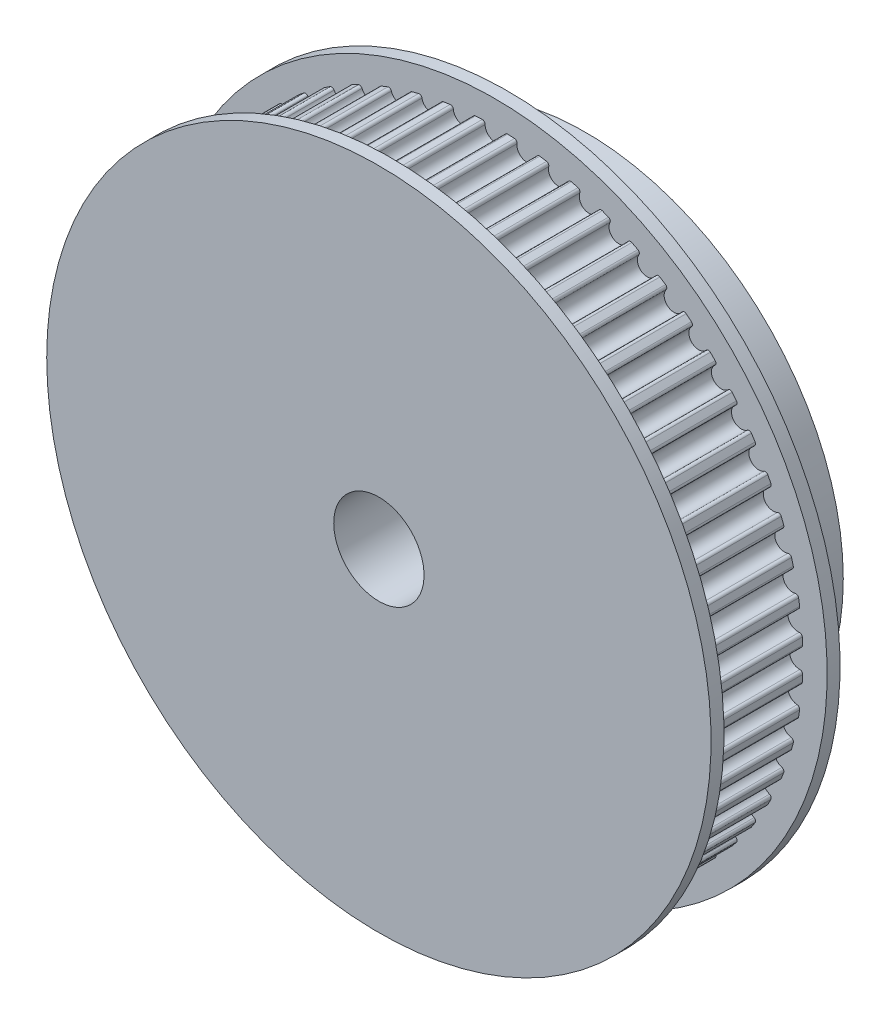
SolidWorks part; units mm, degrees
ref_plane "Front Plane" through (0, 0, 0) normal (0, 0, 1) x (1, 0, 0)
ref_plane "Top Plane" through (0, 0, 0) normal (0, 1, 0) x (1, 0, 0)
ref_plane "Right Plane" through (0, 0, 0) normal (1, 0, 0) x (0, 0, -1)
sketch "Sketch1" plane through (0, 0, 0) normal (0, 0, 1) x (1, 0, 0)
  arc A2 (3.0256, 47.649) -> (1.9717, 47.7043) centre (0, 0) ccw
  arc A3 (0, 45.685) -> (1.5242, 47.2604) centre (0, 47.21) ccw
  arc A4 (1.9717, 47.7043) -> (1.5242, 47.2604) centre (1.9539, 47.2746) ccw
  arc A5 (3.4242, 47.1608) -> (4.7754, 45.4347) centre (4.9348, 46.9514) ccw
  arc A6 (3.4242, 47.1608) -> (3.0256, 47.649) centre (2.9983, 47.2199) ccw
  arc A7 (4.7754, 45.4347) -> (6.4559, 46.8422) centre (4.9348, 46.9514) ccw
  arc A8 (6.9473, 47.2368) -> (6.4559, 46.8422) centre (6.8848, 46.8114) ccw
  arc A9 (7.9897, 47.0718) -> (6.9473, 47.2368) centre (0, 0) ccw
  arc A10 (8.3351, 46.5446) -> (7.9897, 47.0718) centre (7.9177, 46.6478) ccw
  arc A11 (8.3351, 46.5446) -> (9.4984, 44.6867) centre (9.8155, 46.1783) ccw
  arc A12 (9.4984, 44.6867) -> (11.3169, 45.9108) centre (9.8155, 46.1783) ccw
  arc A13 (11.8469, 46.2519) -> (11.3169, 45.9108) centre (11.7402, 45.8353) ccw
  arc A14 (12.8662, 45.9787) -> (11.8469, 46.2519) centre (0, 0) ccw
  arc A15 (13.1547, 45.4183) -> (12.8662, 45.9787) centre (12.7504, 45.5647) ccw
  arc A16 (13.1547, 45.4183) -> (14.1174, 43.449) centre (14.5887, 44.8994) ccw
  arc A17 (14.1174, 43.449) -> (16.0538, 44.4763) centre (14.5887, 44.8994) ccw
  arc A18 (16.6166, 44.7602) -> (16.0538, 44.4763) centre (16.467, 44.3571) ccw
  arc A19 (17.6018, 44.382) -> (16.6166, 44.7602) centre (0, 0) ccw
  arc A20 (17.8301, 43.7945) -> (17.6018, 44.382) centre (17.4433, 43.9823) ccw
  arc A21 (17.8301, 43.7945) -> (18.5818, 41.7353) centre (19.202, 43.1285) ccw
  arc A22 (18.5818, 41.7353) -> (20.6149, 42.5546) centre (19.202, 43.1285) ccw
  arc A23 (21.2043, 42.7781) -> (20.6149, 42.5546) centre (21.0133, 42.3928) ccw
  arc A24 (22.1446, 42.299) -> (21.2043, 42.7781) centre (0, 0) ccw
  arc A25 (22.3102, 41.6908) -> (22.1446, 42.299) centre (21.9452, 41.918) ccw
  arc A26 (22.3102, 41.6908) -> (22.8425, 39.5644) centre (23.605, 40.8851) ccw
  arc A27 (22.8425, 39.5644) -> (24.9502, 40.1666) centre (23.605, 40.8851) ccw
  arc A28 (25.5597, 40.3273) -> (24.9502, 40.1666) centre (25.3295, 39.9641) ccw
  arc A29 (26.4447, 39.7525) -> (25.5597, 40.3273) centre (0, 0) ccw
  arc A30 (26.5459, 39.1304) -> (26.4447, 39.7525) centre (26.2066, 39.3945) ccw
  arc A31 (26.5459, 39.1304) -> (26.853, 36.9599) centre (27.7493, 38.1937) ccw
  arc A32 (26.853, 36.9599) -> (29.0121, 37.3386) centre (27.7493, 38.1937) ccw
  arc A33 (29.635, 37.4346) -> (29.0121, 37.3386) centre (29.3681, 37.0975) ccw
  arc A34 (30.4551, 36.7705) -> (29.635, 37.4346) centre (0, 0) ccw
  arc A35 (30.4907, 36.1412) -> (30.4551, 36.7705) centre (30.1809, 36.4393) ccw
  arc A36 (30.4907, 36.1412) -> (30.5692, 33.9506) centre (31.5897, 35.0839) ccw
  arc A37 (30.5692, 33.9506) -> (32.7561, 34.1015) centre (31.5897, 35.0839) ccw
  arc A38 (33.3856, 34.1319) -> (32.7561, 34.1015) centre (33.085, 33.8245) ccw
  arc A39 (34.1319, 33.3856) -> (33.3856, 34.1319) centre (0, 0) ccw
  arc A40 (34.1015, 32.7561) -> (34.1319, 33.3856) centre (33.8245, 33.085) ccw
  arc A41 (34.1015, 32.7561) -> (33.9506, 30.5692) centre (35.0839, 31.5897) ccw
  arc A42 (33.9506, 30.5692) -> (36.1412, 30.4907) centre (35.0839, 31.5897) ccw
  arc A43 (36.7705, 30.4551) -> (36.1412, 30.4907) centre (36.4393, 30.1809) ccw
  arc A44 (37.4346, 29.635) -> (36.7705, 30.4551) centre (0, 0) ccw
  arc A45 (37.3386, 29.0121) -> (37.4346, 29.635) centre (37.0975, 29.3681) ccw
  arc A46 (37.3386, 29.0121) -> (36.9599, 26.853) centre (38.1937, 27.7493) ccw
  arc A47 (36.9599, 26.853) -> (39.1304, 26.5459) centre (38.1937, 27.7493) ccw
  arc A48 (39.7525, 26.4447) -> (39.1304, 26.5459) centre (39.3945, 26.2066) ccw
  arc A49 (40.3273, 25.5597) -> (39.7525, 26.4447) centre (0, 0) ccw
  arc A50 (40.1666, 24.9502) -> (40.3273, 25.5597) centre (39.9641, 25.3295) ccw
  arc A51 (40.1666, 24.9502) -> (39.5644, 22.8425) centre (40.8851, 23.605) ccw
  arc A52 (39.5644, 22.8425) -> (41.6908, 22.3102) centre (40.8851, 23.605) ccw
  arc A53 (42.299, 22.1446) -> (41.6908, 22.3102) centre (41.918, 21.9452) ccw
  arc A54 (42.7781, 21.2043) -> (42.299, 22.1446) centre (0, 0) ccw
  arc A55 (42.5546, 20.6149) -> (42.7781, 21.2043) centre (42.3928, 21.0133) ccw
  arc A56 (42.5546, 20.6149) -> (41.7353, 18.5818) centre (43.1285, 19.202) ccw
  arc A57 (41.7353, 18.5818) -> (43.7945, 17.8301) centre (43.1285, 19.202) ccw
  arc A58 (44.382, 17.6018) -> (43.7945, 17.8301) centre (43.9823, 17.4433) ccw
  arc A59 (44.7602, 16.6166) -> (44.382, 17.6018) centre (0, 0) ccw
  arc A60 (44.4763, 16.0538) -> (44.7602, 16.6166) centre (44.3571, 16.467) ccw
  arc A61 (44.4763, 16.0538) -> (43.449, 14.1174) centre (44.8994, 14.5887) ccw
  arc A62 (43.449, 14.1174) -> (45.4183, 13.1547) centre (44.8994, 14.5887) ccw
  arc A63 (45.9787, 12.8662) -> (45.4183, 13.1547) centre (45.5647, 12.7504) ccw
  arc A64 (46.2519, 11.8469) -> (45.9787, 12.8662) centre (0, 0) ccw
  arc A65 (45.9108, 11.3169) -> (46.2519, 11.8469) centre (45.8353, 11.7402) ccw
  arc A66 (45.9108, 11.3169) -> (44.6867, 9.4984) centre (46.1783, 9.8155) ccw
  arc A67 (44.6867, 9.4984) -> (46.5446, 8.3351) centre (46.1783, 9.8155) ccw
  arc A68 (47.0718, 7.9897) -> (46.5446, 8.3351) centre (46.6478, 7.9177) ccw
  arc A69 (47.2368, 6.9473) -> (47.0718, 7.9897) centre (0, 0) ccw
  arc A70 (46.8422, 6.4559) -> (47.2368, 6.9473) centre (46.8114, 6.8848) ccw
  arc A71 (46.8422, 6.4559) -> (45.4347, 4.7754) centre (46.9514, 4.9348) ccw
  arc A72 (45.4347, 4.7754) -> (47.1608, 3.4242) centre (46.9514, 4.9348) ccw
  arc A73 (47.649, 3.0256) -> (47.1608, 3.4242) centre (47.2199, 2.9983) ccw
  arc A74 (47.7043, 1.9717) -> (47.649, 3.0256) centre (0, 0) ccw
  arc A75 (47.2604, 1.5242) -> (47.7043, 1.9717) centre (47.2746, 1.9539) ccw
  arc A76 (47.2604, 1.5242) -> (45.685, 0) centre (47.21, 0) ccw
  arc A77 (45.685, 0) -> (47.2604, -1.5242) centre (47.21, 0) ccw
  arc A78 (47.7043, -1.9717) -> (47.2604, -1.5242) centre (47.2746, -1.9539) ccw
  arc A79 (47.649, -3.0256) -> (47.7043, -1.9717) centre (0, 0) ccw
  arc A80 (47.1608, -3.4242) -> (47.649, -3.0256) centre (47.2199, -2.9983) ccw
  arc A81 (47.1608, -3.4242) -> (45.4347, -4.7754) centre (46.9514, -4.9348) ccw
  arc A82 (45.4347, -4.7754) -> (46.8422, -6.4559) centre (46.9514, -4.9348) ccw
  arc A83 (47.2368, -6.9473) -> (46.8422, -6.4559) centre (46.8114, -6.8848) ccw
  arc A84 (47.0718, -7.9897) -> (47.2368, -6.9473) centre (0, 0) ccw
  arc A85 (46.5446, -8.3351) -> (47.0718, -7.9897) centre (46.6478, -7.9177) ccw
  arc A86 (46.5446, -8.3351) -> (44.6867, -9.4984) centre (46.1783, -9.8155) ccw
  arc A87 (44.6867, -9.4984) -> (45.9108, -11.3169) centre (46.1783, -9.8155) ccw
  arc A88 (46.2519, -11.8469) -> (45.9108, -11.3169) centre (45.8353, -11.7402) ccw
  arc A89 (45.9787, -12.8662) -> (46.2519, -11.8469) centre (0, 0) ccw
  arc A90 (45.4183, -13.1547) -> (45.9787, -12.8662) centre (45.5647, -12.7504) ccw
  arc A91 (45.4183, -13.1547) -> (43.449, -14.1174) centre (44.8994, -14.5887) ccw
  arc A92 (43.449, -14.1174) -> (44.4763, -16.0538) centre (44.8994, -14.5887) ccw
  arc A93 (44.7602, -16.6166) -> (44.4763, -16.0538) centre (44.3571, -16.467) ccw
  arc A94 (44.382, -17.6018) -> (44.7602, -16.6166) centre (0, 0) ccw
  arc A95 (43.7945, -17.8301) -> (44.382, -17.6018) centre (43.9823, -17.4433) ccw
  arc A96 (43.7945, -17.8301) -> (41.7353, -18.5818) centre (43.1285, -19.202) ccw
  arc A97 (41.7353, -18.5818) -> (42.5546, -20.6149) centre (43.1285, -19.202) ccw
  arc A98 (42.7781, -21.2043) -> (42.5546, -20.6149) centre (42.3928, -21.0133) ccw
  arc A99 (42.299, -22.1446) -> (42.7781, -21.2043) centre (0, 0) ccw
  arc A100 (41.6908, -22.3102) -> (42.299, -22.1446) centre (41.918, -21.9452) ccw
  arc A101 (41.6908, -22.3102) -> (39.5644, -22.8425) centre (40.8851, -23.605) ccw
  arc A102 (39.5644, -22.8425) -> (40.1666, -24.9502) centre (40.8851, -23.605) ccw
  arc A103 (40.3273, -25.5597) -> (40.1666, -24.9502) centre (39.9641, -25.3295) ccw
  arc A104 (39.7525, -26.4447) -> (40.3273, -25.5597) centre (0, 0) ccw
  arc A105 (39.1304, -26.5459) -> (39.7525, -26.4447) centre (39.3945, -26.2066) ccw
  arc A106 (39.1304, -26.5459) -> (36.9599, -26.853) centre (38.1937, -27.7493) ccw
  arc A107 (36.9599, -26.853) -> (37.3386, -29.0121) centre (38.1937, -27.7493) ccw
  arc A108 (37.4346, -29.635) -> (37.3386, -29.0121) centre (37.0975, -29.3681) ccw
  arc A109 (36.7705, -30.4551) -> (37.4346, -29.635) centre (0, 0) ccw
  arc A110 (36.1412, -30.4907) -> (36.7705, -30.4551) centre (36.4393, -30.1809) ccw
  arc A111 (36.1412, -30.4907) -> (33.9506, -30.5692) centre (35.0839, -31.5897) ccw
  arc A112 (33.9506, -30.5692) -> (34.1015, -32.7561) centre (35.0839, -31.5897) ccw
  arc A113 (34.1319, -33.3856) -> (34.1015, -32.7561) centre (33.8245, -33.085) ccw
  arc A114 (33.3856, -34.1319) -> (34.1319, -33.3856) centre (0, 0) ccw
  arc A115 (32.7561, -34.1015) -> (33.3856, -34.1319) centre (33.085, -33.8245) ccw
  arc A116 (32.7561, -34.1015) -> (30.5692, -33.9506) centre (31.5897, -35.0839) ccw
  arc A117 (30.5692, -33.9506) -> (30.4907, -36.1412) centre (31.5897, -35.0839) ccw
  arc A118 (30.4551, -36.7705) -> (30.4907, -36.1412) centre (30.1809, -36.4393) ccw
  arc A119 (29.635, -37.4346) -> (30.4551, -36.7705) centre (0, 0) ccw
  arc A120 (29.0121, -37.3386) -> (29.635, -37.4346) centre (29.3681, -37.0975) ccw
  arc A121 (29.0121, -37.3386) -> (26.853, -36.9599) centre (27.7493, -38.1937) ccw
  arc A122 (26.853, -36.9599) -> (26.5459, -39.1304) centre (27.7493, -38.1937) ccw
  arc A123 (26.4447, -39.7525) -> (26.5459, -39.1304) centre (26.2066, -39.3945) ccw
  arc A124 (25.5597, -40.3273) -> (26.4447, -39.7525) centre (0, 0) ccw
  arc A125 (24.9502, -40.1666) -> (25.5597, -40.3273) centre (25.3295, -39.9641) ccw
  arc A126 (24.9502, -40.1666) -> (22.8425, -39.5644) centre (23.605, -40.8851) ccw
  arc A127 (22.8425, -39.5644) -> (22.3102, -41.6908) centre (23.605, -40.8851) ccw
  arc A128 (22.1446, -42.299) -> (22.3102, -41.6908) centre (21.9452, -41.918) ccw
  arc A129 (21.2043, -42.7781) -> (22.1446, -42.299) centre (0, 0) ccw
  arc A130 (20.6149, -42.5546) -> (21.2043, -42.7781) centre (21.0133, -42.3928) ccw
  arc A131 (20.6149, -42.5546) -> (18.5818, -41.7353) centre (19.202, -43.1285) ccw
  arc A132 (18.5818, -41.7353) -> (17.8301, -43.7945) centre (19.202, -43.1285) ccw
  arc A133 (17.6018, -44.382) -> (17.8301, -43.7945) centre (17.4433, -43.9823) ccw
  arc A134 (16.6166, -44.7602) -> (17.6018, -44.382) centre (0, 0) ccw
  arc A135 (16.0538, -44.4763) -> (16.6166, -44.7602) centre (16.467, -44.3571) ccw
  arc A136 (16.0538, -44.4763) -> (14.1174, -43.449) centre (14.5887, -44.8994) ccw
  arc A137 (14.1174, -43.449) -> (13.1547, -45.4183) centre (14.5887, -44.8994) ccw
  arc A138 (12.8662, -45.9787) -> (13.1547, -45.4183) centre (12.7504, -45.5647) ccw
  arc A139 (11.8469, -46.2519) -> (12.8662, -45.9787) centre (0, 0) ccw
  arc A140 (11.3169, -45.9108) -> (11.8469, -46.2519) centre (11.7402, -45.8353) ccw
  arc A141 (11.3169, -45.9108) -> (9.4984, -44.6867) centre (9.8155, -46.1783) ccw
  arc A142 (9.4984, -44.6867) -> (8.3351, -46.5446) centre (9.8155, -46.1783) ccw
  arc A143 (7.9897, -47.0718) -> (8.3351, -46.5446) centre (7.9177, -46.6478) ccw
  arc A144 (6.9473, -47.2368) -> (7.9897, -47.0718) centre (0, 0) ccw
  arc A145 (6.4559, -46.8422) -> (6.9473, -47.2368) centre (6.8848, -46.8114) ccw
  arc A146 (6.4559, -46.8422) -> (4.7754, -45.4347) centre (4.9348, -46.9514) ccw
  arc A147 (4.7754, -45.4347) -> (3.4242, -47.1608) centre (4.9348, -46.9514) ccw
  arc A148 (3.0256, -47.649) -> (3.4242, -47.1608) centre (2.9983, -47.2199) ccw
  arc A149 (1.9717, -47.7043) -> (3.0256, -47.649) centre (0, 0) ccw
  arc A150 (1.5242, -47.2604) -> (1.9717, -47.7043) centre (1.9539, -47.2746) ccw
  arc A151 (1.5242, -47.2604) -> (0, -45.685) centre (0, -47.21) ccw
  arc A152 (0, -45.685) -> (-1.5242, -47.2604) centre (0, -47.21) ccw
  arc A153 (-1.9717, -47.7043) -> (-1.5242, -47.2604) centre (-1.9539, -47.2746) ccw
  arc A154 (-3.0256, -47.649) -> (-1.9717, -47.7043) centre (0, 0) ccw
  arc A155 (-3.4242, -47.1608) -> (-3.0256, -47.649) centre (-2.9983, -47.2199) ccw
  arc A156 (-3.4242, -47.1608) -> (-4.7754, -45.4347) centre (-4.9348, -46.9514) ccw
  arc A157 (-4.7754, -45.4347) -> (-6.4559, -46.8422) centre (-4.9348, -46.9514) ccw
  arc A158 (-6.9473, -47.2368) -> (-6.4559, -46.8422) centre (-6.8848, -46.8114) ccw
  arc A159 (-7.9897, -47.0718) -> (-6.9473, -47.2368) centre (0, 0) ccw
  arc A160 (-8.3351, -46.5446) -> (-7.9897, -47.0718) centre (-7.9177, -46.6478) ccw
  arc A161 (-8.3351, -46.5446) -> (-9.4984, -44.6867) centre (-9.8155, -46.1783) ccw
  arc A162 (-9.4984, -44.6867) -> (-11.3169, -45.9108) centre (-9.8155, -46.1783) ccw
  arc A163 (-11.8469, -46.2519) -> (-11.3169, -45.9108) centre (-11.7402, -45.8353) ccw
  arc A164 (-12.8662, -45.9787) -> (-11.8469, -46.2519) centre (0, 0) ccw
  arc A165 (-13.1547, -45.4183) -> (-12.8662, -45.9787) centre (-12.7504, -45.5647) ccw
  arc A166 (-13.1547, -45.4183) -> (-14.1174, -43.449) centre (-14.5887, -44.8994) ccw
  arc A167 (-14.1174, -43.449) -> (-16.0538, -44.4763) centre (-14.5887, -44.8994) ccw
  arc A168 (-16.6166, -44.7602) -> (-16.0538, -44.4763) centre (-16.467, -44.3571) ccw
  arc A169 (-17.6018, -44.382) -> (-16.6166, -44.7602) centre (0, 0) ccw
  arc A170 (-17.8301, -43.7945) -> (-17.6018, -44.382) centre (-17.4433, -43.9823) ccw
  arc A171 (-17.8301, -43.7945) -> (-18.5818, -41.7353) centre (-19.202, -43.1285) ccw
  arc A172 (-18.5818, -41.7353) -> (-20.6149, -42.5546) centre (-19.202, -43.1285) ccw
  arc A173 (-21.2043, -42.7781) -> (-20.6149, -42.5546) centre (-21.0133, -42.3928) ccw
  arc A174 (-22.1446, -42.299) -> (-21.2043, -42.7781) centre (0, 0) ccw
  arc A175 (-22.3102, -41.6908) -> (-22.1446, -42.299) centre (-21.9452, -41.918) ccw
  arc A176 (-22.3102, -41.6908) -> (-22.8425, -39.5644) centre (-23.605, -40.8851) ccw
  arc A177 (-22.8425, -39.5644) -> (-24.9502, -40.1666) centre (-23.605, -40.8851) ccw
  arc A178 (-25.5597, -40.3273) -> (-24.9502, -40.1666) centre (-25.3295, -39.9641) ccw
  arc A179 (-26.4447, -39.7525) -> (-25.5597, -40.3273) centre (0, 0) ccw
  arc A180 (-26.5459, -39.1304) -> (-26.4447, -39.7525) centre (-26.2066, -39.3945) ccw
  arc A181 (-26.5459, -39.1304) -> (-26.853, -36.9599) centre (-27.7493, -38.1937) ccw
  arc A182 (-26.853, -36.9599) -> (-29.0121, -37.3386) centre (-27.7493, -38.1937) ccw
  arc A183 (-29.635, -37.4346) -> (-29.0121, -37.3386) centre (-29.3681, -37.0975) ccw
  arc A184 (-30.4551, -36.7705) -> (-29.635, -37.4346) centre (0, 0) ccw
  arc A185 (-30.4907, -36.1412) -> (-30.4551, -36.7705) centre (-30.1809, -36.4393) ccw
  arc A186 (-30.4907, -36.1412) -> (-30.5692, -33.9506) centre (-31.5897, -35.0839) ccw
  arc A187 (-30.5692, -33.9506) -> (-32.7561, -34.1015) centre (-31.5897, -35.0839) ccw
  arc A188 (-33.3856, -34.1319) -> (-32.7561, -34.1015) centre (-33.085, -33.8245) ccw
  arc A189 (-34.1319, -33.3856) -> (-33.3856, -34.1319) centre (0, 0) ccw
  arc A190 (-34.1015, -32.7561) -> (-34.1319, -33.3856) centre (-33.8245, -33.085) ccw
  arc A191 (-34.1015, -32.7561) -> (-33.9506, -30.5692) centre (-35.0839, -31.5897) ccw
  arc A192 (-33.9506, -30.5692) -> (-36.1412, -30.4907) centre (-35.0839, -31.5897) ccw
  arc A193 (-36.7705, -30.4551) -> (-36.1412, -30.4907) centre (-36.4393, -30.1809) ccw
  arc A194 (-37.4346, -29.635) -> (-36.7705, -30.4551) centre (0, 0) ccw
  arc A195 (-37.3386, -29.0121) -> (-37.4346, -29.635) centre (-37.0975, -29.3681) ccw
  arc A196 (-37.3386, -29.0121) -> (-36.9599, -26.853) centre (-38.1937, -27.7493) ccw
  arc A197 (-36.9599, -26.853) -> (-39.1304, -26.5459) centre (-38.1937, -27.7493) ccw
  arc A198 (-39.7525, -26.4447) -> (-39.1304, -26.5459) centre (-39.3945, -26.2066) ccw
  arc A199 (-40.3273, -25.5597) -> (-39.7525, -26.4447) centre (0, 0) ccw
  arc A200 (-40.1666, -24.9502) -> (-40.3273, -25.5597) centre (-39.9641, -25.3295) ccw
  arc A201 (-40.1666, -24.9502) -> (-39.5644, -22.8425) centre (-40.8851, -23.605) ccw
  arc A202 (-39.5644, -22.8425) -> (-41.6908, -22.3102) centre (-40.8851, -23.605) ccw
  arc A203 (-42.299, -22.1446) -> (-41.6908, -22.3102) centre (-41.918, -21.9452) ccw
  arc A204 (-42.7781, -21.2043) -> (-42.299, -22.1446) centre (0, 0) ccw
  arc A205 (-42.5546, -20.6149) -> (-42.7781, -21.2043) centre (-42.3928, -21.0133) ccw
  arc A206 (-42.5546, -20.6149) -> (-41.7353, -18.5818) centre (-43.1285, -19.202) ccw
  arc A207 (-41.7353, -18.5818) -> (-43.7945, -17.8301) centre (-43.1285, -19.202) ccw
  arc A208 (-44.382, -17.6018) -> (-43.7945, -17.8301) centre (-43.9823, -17.4433) ccw
  arc A209 (-44.7602, -16.6166) -> (-44.382, -17.6018) centre (0, 0) ccw
  arc A210 (-44.4763, -16.0538) -> (-44.7602, -16.6166) centre (-44.3571, -16.467) ccw
  arc A211 (-44.4763, -16.0538) -> (-43.449, -14.1174) centre (-44.8994, -14.5887) ccw
  arc A212 (-43.449, -14.1174) -> (-45.4183, -13.1547) centre (-44.8994, -14.5887) ccw
  arc A213 (-45.9787, -12.8662) -> (-45.4183, -13.1547) centre (-45.5647, -12.7504) ccw
  arc A214 (-46.2519, -11.8469) -> (-45.9787, -12.8662) centre (0, 0) ccw
  arc A215 (-45.9108, -11.3169) -> (-46.2519, -11.8469) centre (-45.8353, -11.7402) ccw
  arc A216 (-45.9108, -11.3169) -> (-44.6867, -9.4984) centre (-46.1783, -9.8155) ccw
  arc A217 (-44.6867, -9.4984) -> (-46.5446, -8.3351) centre (-46.1783, -9.8155) ccw
  arc A218 (-47.0718, -7.9897) -> (-46.5446, -8.3351) centre (-46.6478, -7.9177) ccw
  arc A219 (-47.2368, -6.9473) -> (-47.0718, -7.9897) centre (0, 0) ccw
  arc A220 (-46.8422, -6.4559) -> (-47.2368, -6.9473) centre (-46.8114, -6.8848) ccw
  arc A221 (-46.8422, -6.4559) -> (-45.4347, -4.7754) centre (-46.9514, -4.9348) ccw
  arc A222 (-45.4347, -4.7754) -> (-47.1608, -3.4242) centre (-46.9514, -4.9348) ccw
  arc A223 (-47.649, -3.0256) -> (-47.1608, -3.4242) centre (-47.2199, -2.9983) ccw
  arc A224 (-47.7043, -1.9717) -> (-47.649, -3.0256) centre (0, 0) ccw
  arc A225 (-47.2604, -1.5242) -> (-47.7043, -1.9717) centre (-47.2746, -1.9539) ccw
  arc A226 (-47.2604, -1.5242) -> (-45.685, 0) centre (-47.21, 0) ccw
  arc A227 (-45.685, 0) -> (-47.2604, 1.5242) centre (-47.21, 0) ccw
  arc A228 (-47.7043, 1.9717) -> (-47.2604, 1.5242) centre (-47.2746, 1.9539) ccw
  arc A229 (-47.649, 3.0256) -> (-47.7043, 1.9717) centre (0, 0) ccw
  arc A230 (-47.1608, 3.4242) -> (-47.649, 3.0256) centre (-47.2199, 2.9983) ccw
  arc A231 (-47.1608, 3.4242) -> (-45.4347, 4.7754) centre (-46.9514, 4.9348) ccw
  arc A232 (-45.4347, 4.7754) -> (-46.8422, 6.4559) centre (-46.9514, 4.9348) ccw
  arc A233 (-47.2368, 6.9473) -> (-46.8422, 6.4559) centre (-46.8114, 6.8848) ccw
  arc A234 (-47.0718, 7.9897) -> (-47.2368, 6.9473) centre (0, 0) ccw
  arc A235 (-46.5446, 8.3351) -> (-47.0718, 7.9897) centre (-46.6478, 7.9177) ccw
  arc A236 (-46.5446, 8.3351) -> (-44.6867, 9.4984) centre (-46.1783, 9.8155) ccw
  arc A237 (-44.6867, 9.4984) -> (-45.9108, 11.3169) centre (-46.1783, 9.8155) ccw
  arc A238 (-46.2519, 11.8469) -> (-45.9108, 11.3169) centre (-45.8353, 11.7402) ccw
  arc A239 (-45.9787, 12.8662) -> (-46.2519, 11.8469) centre (0, 0) ccw
  arc A240 (-45.4183, 13.1547) -> (-45.9787, 12.8662) centre (-45.5647, 12.7504) ccw
  arc A241 (-45.4183, 13.1547) -> (-43.449, 14.1174) centre (-44.8994, 14.5887) ccw
  arc A242 (-43.449, 14.1174) -> (-44.4763, 16.0538) centre (-44.8994, 14.5887) ccw
  arc A243 (-44.7602, 16.6166) -> (-44.4763, 16.0538) centre (-44.3571, 16.467) ccw
  arc A244 (-44.382, 17.6018) -> (-44.7602, 16.6166) centre (0, 0) ccw
  arc A245 (-43.7945, 17.8301) -> (-44.382, 17.6018) centre (-43.9823, 17.4433) ccw
  arc A246 (-43.7945, 17.8301) -> (-41.7353, 18.5818) centre (-43.1285, 19.202) ccw
  arc A247 (-41.7353, 18.5818) -> (-42.5546, 20.6149) centre (-43.1285, 19.202) ccw
  arc A248 (-42.7781, 21.2043) -> (-42.5546, 20.6149) centre (-42.3928, 21.0133) ccw
  arc A249 (-42.299, 22.1446) -> (-42.7781, 21.2043) centre (0, 0) ccw
  arc A250 (-41.6908, 22.3102) -> (-42.299, 22.1446) centre (-41.918, 21.9452) ccw
  arc A251 (-41.6908, 22.3102) -> (-39.5644, 22.8425) centre (-40.8851, 23.605) ccw
  arc A252 (-39.5644, 22.8425) -> (-40.1666, 24.9502) centre (-40.8851, 23.605) ccw
  arc A253 (-40.3273, 25.5597) -> (-40.1666, 24.9502) centre (-39.9641, 25.3295) ccw
  arc A254 (-39.7525, 26.4447) -> (-40.3273, 25.5597) centre (0, 0) ccw
  arc A255 (-39.1304, 26.5459) -> (-39.7525, 26.4447) centre (-39.3945, 26.2066) ccw
  arc A256 (-39.1304, 26.5459) -> (-36.9599, 26.853) centre (-38.1937, 27.7493) ccw
  arc A257 (-36.9599, 26.853) -> (-37.3386, 29.0121) centre (-38.1937, 27.7493) ccw
  arc A258 (-37.4346, 29.635) -> (-37.3386, 29.0121) centre (-37.0975, 29.3681) ccw
  arc A259 (-36.7705, 30.4551) -> (-37.4346, 29.635) centre (0, 0) ccw
  arc A260 (-36.1412, 30.4907) -> (-36.7705, 30.4551) centre (-36.4393, 30.1809) ccw
  arc A261 (-36.1412, 30.4907) -> (-33.9506, 30.5692) centre (-35.0839, 31.5897) ccw
  arc A262 (-33.9506, 30.5692) -> (-34.1015, 32.7561) centre (-35.0839, 31.5897) ccw
  arc A263 (-34.1319, 33.3856) -> (-34.1015, 32.7561) centre (-33.8245, 33.085) ccw
  arc A264 (-33.3856, 34.1319) -> (-34.1319, 33.3856) centre (0, 0) ccw
  arc A265 (-32.7561, 34.1015) -> (-33.3856, 34.1319) centre (-33.085, 33.8245) ccw
  arc A266 (-32.7561, 34.1015) -> (-30.5692, 33.9506) centre (-31.5897, 35.0839) ccw
  arc A267 (-30.5692, 33.9506) -> (-30.4907, 36.1412) centre (-31.5897, 35.0839) ccw
  arc A268 (-30.4551, 36.7705) -> (-30.4907, 36.1412) centre (-30.1809, 36.4393) ccw
  arc A269 (-29.635, 37.4346) -> (-30.4551, 36.7705) centre (0, 0) ccw
  arc A270 (-29.0121, 37.3386) -> (-29.635, 37.4346) centre (-29.3681, 37.0975) ccw
  arc A271 (-29.0121, 37.3386) -> (-26.853, 36.9599) centre (-27.7493, 38.1937) ccw
  arc A272 (-26.853, 36.9599) -> (-26.5459, 39.1304) centre (-27.7493, 38.1937) ccw
  arc A273 (-26.4447, 39.7525) -> (-26.5459, 39.1304) centre (-26.2066, 39.3945) ccw
  arc A274 (-25.5597, 40.3273) -> (-26.4447, 39.7525) centre (0, 0) ccw
  arc A275 (-24.9502, 40.1666) -> (-25.5597, 40.3273) centre (-25.3295, 39.9641) ccw
  arc A276 (-24.9502, 40.1666) -> (-22.8425, 39.5644) centre (-23.605, 40.8851) ccw
  arc A277 (-22.8425, 39.5644) -> (-22.3102, 41.6908) centre (-23.605, 40.8851) ccw
  arc A278 (-22.1446, 42.299) -> (-22.3102, 41.6908) centre (-21.9452, 41.918) ccw
  arc A279 (-21.2043, 42.7781) -> (-22.1446, 42.299) centre (0, 0) ccw
  arc A280 (-20.6149, 42.5546) -> (-21.2043, 42.7781) centre (-21.0133, 42.3928) ccw
  arc A281 (-20.6149, 42.5546) -> (-18.5818, 41.7353) centre (-19.202, 43.1285) ccw
  arc A282 (-18.5818, 41.7353) -> (-17.8301, 43.7945) centre (-19.202, 43.1285) ccw
  arc A283 (-17.6018, 44.382) -> (-17.8301, 43.7945) centre (-17.4433, 43.9823) ccw
  arc A284 (-16.6166, 44.7602) -> (-17.6018, 44.382) centre (0, 0) ccw
  arc A285 (-16.0538, 44.4763) -> (-16.6166, 44.7602) centre (-16.467, 44.3571) ccw
  arc A286 (-16.0538, 44.4763) -> (-14.1174, 43.449) centre (-14.5887, 44.8994) ccw
  arc A287 (-14.1174, 43.449) -> (-13.1547, 45.4183) centre (-14.5887, 44.8994) ccw
  arc A288 (-12.8662, 45.9787) -> (-13.1547, 45.4183) centre (-12.7504, 45.5647) ccw
  arc A289 (-11.8469, 46.2519) -> (-12.8662, 45.9787) centre (0, 0) ccw
  arc A290 (-11.3169, 45.9108) -> (-11.8469, 46.2519) centre (-11.7402, 45.8353) ccw
  arc A291 (-11.3169, 45.9108) -> (-9.4984, 44.6867) centre (-9.8155, 46.1783) ccw
  arc A292 (-9.4984, 44.6867) -> (-8.3351, 46.5446) centre (-9.8155, 46.1783) ccw
  arc A293 (-7.9897, 47.0718) -> (-8.3351, 46.5446) centre (-7.9177, 46.6478) ccw
  arc A294 (-6.9473, 47.2368) -> (-7.9897, 47.0718) centre (0, 0) ccw
  arc A295 (-6.4559, 46.8422) -> (-6.9473, 47.2368) centre (-6.8848, 46.8114) ccw
  arc A296 (-6.4559, 46.8422) -> (-4.7754, 45.4347) centre (-4.9348, 46.9514) ccw
  arc A297 (-4.7754, 45.4347) -> (-3.4242, 47.1608) centre (-4.9348, 46.9514) ccw
  arc A298 (-3.0256, 47.649) -> (-3.4242, 47.1608) centre (-2.9983, 47.2199) ccw
  arc A299 (-1.9717, 47.7043) -> (-3.0256, 47.649) centre (0, 0) ccw
  arc A300 (-1.5242, 47.2604) -> (-1.9717, 47.7043) centre (-1.9539, 47.2746) ccw
  arc A301 (-1.5242, 47.2604) -> (0, 45.685) centre (0, 47.21) ccw
  point P607 (0, 0)
  dimension "D1" = 95.49
  dimension "D3" = 3.05
  dimension "D4" = 0.86
  dimension "D6" = 3.05
  dimension "D7" = 0.86
  dimension "D8" = 60
extrude "Boss-Extrude1" add sketch "Sketch1" along normal blind 16
sketch "Sketch3" plane through (0, 0, 0) normal (0, 0, -1) x (-1, 0, 0)
  circle A0 centre (0, 0) radius 51.5
  dimension "D1" = 103
extrude "Boss-Extrude2" add sketch "Sketch3" along normal blind 2
ref_plane "Plane1" through (0, 0, 8) normal (0, 0, 1) x (1, 0, 0)
mirror "Mirror1" about plane through (0, 0, 8) normal (0, 0, 1) of "Boss-Extrude2"
sketch "Sketch4" plane through (0, 0, -2) normal (0, 0, -1) x (-1, 0, 0)
  circle A0 centre (0, 0) radius 40
  dimension "D1" = 80
extrude "Boss-Extrude3" add sketch "Sketch4" along normal blind 12
sketch "Sketch5" plane through (0, 0, -14) normal (0, 0, -1) x (-1, 0, 0)
  circle A0 centre (0, 0) radius 7
  dimension "D1" = 14
extrude "Cut-Extrude1" cut sketch "Sketch5" against normal through all
sketch "Sketch7" plane through (0, 0, 0) normal (1, 0, 0) x (0, 0, -1)
  line L0 (2, -51.5) -> (2, 51.5) construction
  circle A0 centre (7.5, 0) radius 2
  dimension "D1" = 4
  dimension "D2" = 5.5
extrude "Cut-Extrude2" cut sketch "Sketch7" against normal through all both and the other way through all
sketch "Sketch8" plane through (0, 0, -14) normal (0, 0, -1) x (-1, 0, 0)
  line L0 (-33.3379, 0) -> (31.425, 0)
